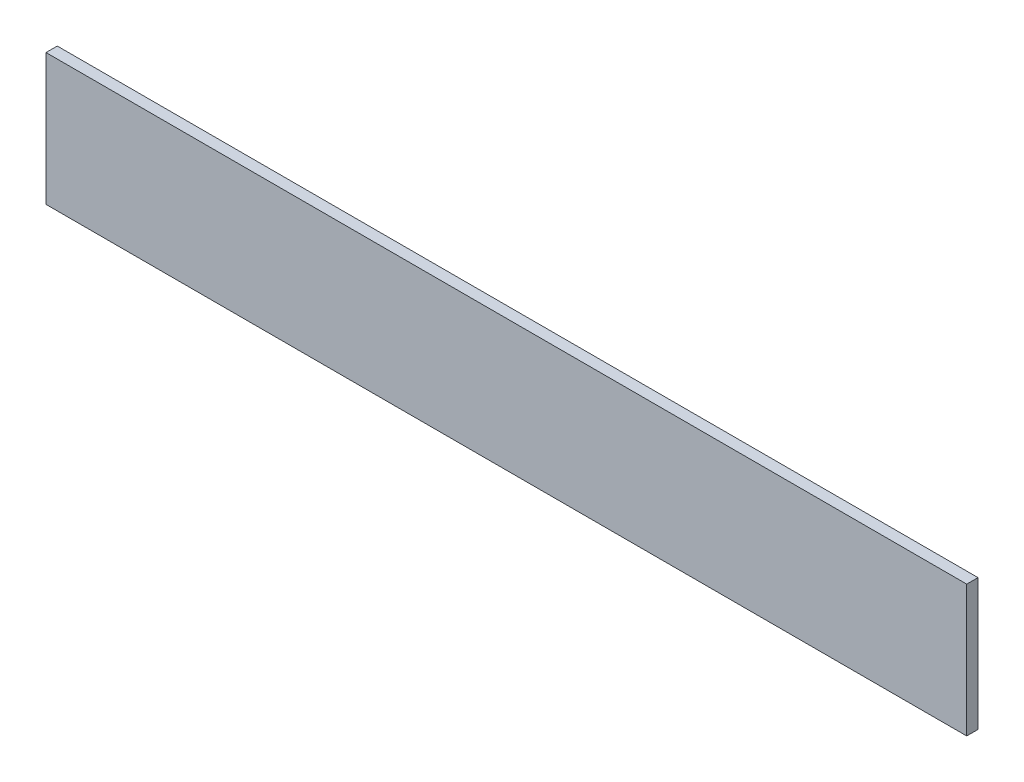
SolidWorks part; units mm, degrees
ref_plane "前视基准面" through (0, 0, 0) normal (0, 0, 1) x (1, 0, 0)
ref_plane "上视基准面" through (0, 0, 0) normal (0, 1, 0) x (1, 0, 0)
ref_plane "右视基准面" through (0, 0, 0) normal (1, 0, 0) x (0, 0, -1)
sketch "草图1" plane through (0, 0, 0) normal (0, 0, 1) x (1, 0, 0)
  line L1 (0, 0) -> (-245, 0)
  line L2 (0, 0) -> (0, -35)
  line L3 (0, -35) -> (-245, -35)
  line L4 (-245, 0) -> (-245, -35)
  dimension "D1" = 245
  dimension "D2" = 35
extrude "凸台-拉伸1" add sketch "草图1" along normal blind 3
